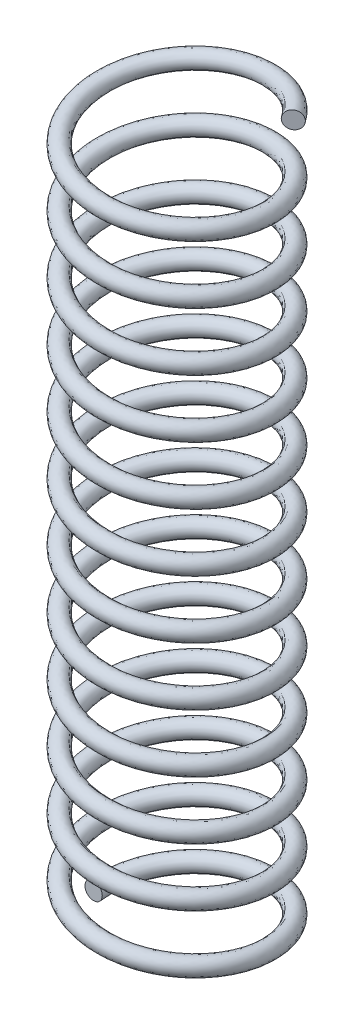
SolidWorks part; units mm, degrees
ref_plane "Front Plane" through (0, 0, 0) normal (0, 0, 1) x (1, 0, 0)
ref_plane "Top Plane" through (0, 0, 0) normal (0, 1, 0) x (1, 0, 0)
ref_plane "Right Plane" through (0, 0, 0) normal (1, 0, 0) x (0, 0, -1)
sketch "Sketch1" plane through (0, 0, 0) normal (0, 1, 0) x (1, 0, 0)
  circle A0 centre (0, 0) radius 5.7531
  dimension "D1" = 11.5062
curve "Helix/Spiral1" pitch 4 height 49.6062 turns 12.4016
sketch "Sketch2" plane through (0, 0, 0) normal (0, 0, 1) x (1, 0, 0)
  circle A0 centre (-5.7531, 0) radius 0.5969
  spline S0 degree 3 poles (-5.7531, 0) (-5.7531, 0.083) (-5.4522, 0.2508) (-4.1674, 0.501) (-2.2454, 0.7516) (0.0199, 1.0021) (2.2821, 1.2527) (4.1955, 1.5032) (5.4674, 1.7538) (5.9034, 2.0043) (5.4369, 2.2548) (4.1391, 2.5054) (2.2085, 2.7559) (-0.0597, 3.0064) (-2.3188, 3.257) (-4.2234, 3.5075) (-5.4823, 3.758) (-5.903, 4.0086) (-5.4212, 4.2591) (-4.1106, 4.5097) (-2.1716, 4.7602) (0.0995, 5.0107) (2.3553, 5.2613) (4.2511, 5.5118) (5.4969, 5.7623) (5.9023, 6.0129) (5.4054, 6.2634) (4.082, 6.5139) (2.1345, 6.7645) (-0.1393, 7.015) (-2.3918, 7.2656) (-4.2786, 7.5161) (-5.5113, 7.7666) (-5.9014, 8.0172) (-5.3892, 8.2677) (-4.0531, 8.5182) (-2.0974, 8.7688) (0.179, 9.0193) (2.4281, 9.2698) (4.3059, 9.5204) (5.5254, 9.7709) (5.9002, 10.0215) (5.3729, 10.272) (4.0241, 10.5225) (2.0601, 10.7731) (-0.2188, 11.0236) (-2.4643, 11.2741) (-4.333, 11.5247) (-5.5393, 11.7752) (-5.8987, 12.0257) (-5.3563, 12.2763) (-3.9949, 12.5268) (-2.0228, 12.7774) (0.2586, 13.0279) (2.5004, 13.2784) (4.36, 13.529) (5.5529, 13.7795) (5.897, 14.03) (5.3394, 14.2806) (3.9655, 14.5311) (1.9854, 14.7816) (-0.2983, 15.0322) (-2.5364, 15.2827) (-4.3867, 15.5333) (-5.5663, 15.7838) (-5.8949, 16.0343) (-5.3223, 16.2849) (-3.936, 16.5354) (-1.9479, 16.7859) (0.338, 17.0365) (2.5723, 17.287) (4.4132, 17.5375) (5.5795, 17.7881) (5.8927, 18.0386) (5.305, 18.2892) (3.9062, 18.5397) (1.9103, 18.7902) (-0.3778, 19.0408) (-2.608, 19.2913) (-4.4395, 19.5418) (-5.5923, 19.7924) (-5.8901, 20.0429) (-5.2874, 20.2934) (-3.8763, 20.544) (-1.8726, 20.7945) (0.4175, 21.0451) (2.6437, 21.2956) (4.4657, 21.5461) (5.605, 21.7967) (5.8873, 22.0472) (5.2696, 22.2977) (3.8462, 22.5483) (1.8348, 22.7988) (-0.4571, 23.0493) (-2.6792, 23.2999) (-4.4916, 23.5504) (-5.6173, 23.801) (-5.8842, 24.0515) (-5.2515, 24.302) (-3.8159, 24.5526) (-1.7969, 24.8031) (0.4968, 25.0536) (2.7146, 25.3042) (4.5173, 25.5547) (5.6294, 25.8052) (5.8809, 26.0558) (5.2332, 26.3063) (3.7855, 26.5569) (1.759, 26.8074) (-0.5364, 27.0579) (-2.7498, 27.3085) (-4.5428, 27.559) (-5.6413, 27.8095) (-5.8773, 28.0601) (-5.2147, 28.3106) (-3.7549, 28.5611) (-1.721, 28.8117) (0.576, 29.0622) (2.785, 29.3128) (4.5681, 29.5633) (5.6529, 29.8138) (5.8734, 30.0644) (5.1959, 30.3149) (3.7241, 30.5654) (1.6829, 30.816) (-0.6156, 31.0665) (-2.82, 31.317) (-4.5932, 31.5676) (-5.6642, 31.8181) (-5.8692, 32.0687) (-5.1769, 32.3192) (-3.6931, 32.5697) (-1.6447, 32.8203) (0.6552, 33.0708) (2.8549, 33.3213) (4.6181, 33.5719) (5.6753, 33.8224) (5.8648, 34.0729) (5.1577, 34.3235) (3.662, 34.574) (1.6064, 34.8246) (-0.6947, 35.0751) (-2.8897, 35.3256) (-4.6428, 35.5762) (-5.6861, 35.8267) (-5.8601, 36.0772) (-5.1382, 36.3278) (-3.6307, 36.5783) (-1.5681, 36.8288) (0.7342, 37.0794) (2.9243, 37.3299) (4.6673, 37.5805) (5.6967, 37.831) (5.8552, 38.0815) (5.1185, 38.3321) (3.5992, 38.5826) (1.5297, 38.8331) (-0.7737, 39.0837) (-2.9588, 39.3342) (-4.6915, 39.5847) (-5.707, 39.8353) (-5.85, 40.0858) (-5.0985, 40.3364) (-3.5676, 40.5869) (-1.4912, 40.8374) (0.8131, 41.088) (2.9932, 41.3385) (4.7156, 41.589) (5.7171, 41.8396) (5.8445, 42.0901) (5.0784, 42.3406) (3.5358, 42.5912) (1.4527, 42.8417) (-0.8525, 43.0923) (-3.0274, 43.3428) (-4.7394, 43.5933) (-5.7269, 43.8439) (-5.8387, 44.0944) (-5.058, 44.3449) (-3.5039, 44.5955) (-1.4141, 44.846) (0.8919, 45.0965) (3.0615, 45.3471) (4.763, 45.5976) (5.7364, 45.8482) (5.8327, 46.0987) (5.0373, 46.3492) (3.4718, 46.5998) (1.3754, 46.8503) (-0.9312, 47.1008) (-3.0954, 47.3514) (-4.7864, 47.6019) (-5.7457, 47.8524) (-5.8265, 48.103) (-5.0165, 48.3535) (-3.4395, 48.6041) (-1.3368, 48.8546) (0.9708, 49.1052) (3.128, 49.3554) (4.2522, 49.5232) (4.6871, 49.6062) knots 0 0 0 0 0.005051 0.010101 0.015152 0.020202 0.025253 0.030303 0.035354 0.040404 0.045455 0.050505 0.055556 0.060606 0.065657 0.070707 0.075758 0.080808 0.085859 0.090909 0.09596 0.10101 0.106061 0.111111 0.116162 0.121212 0.126263 0.131313 0.136364 0.141414 0.146465 0.151515 0.156566 0.161616 0.166667 0.171717 0.176768 0.181818 0.186869 0.191919 0.19697 0.20202 0.207071 0.212121 0.217172 0.222222 0.227273 0.232323 0.237374 0.242424 0.247475 0.252525 0.257576 0.262626 0.267677 0.272727 0.277778 0.282828 0.287879 0.292929 0.29798 0.30303 0.308081 0.313131 0.318182 0.323232 0.328283 0.333333 0.338384 0.343434 0.348485 0.353535 0.358586 0.363636 0.368687 0.373737 0.378788 0.383838 0.388889 0.393939 0.39899 0.40404 0.409091 0.414141 0.419192 0.424242 0.429293 0.434343 0.439394 0.444444 0.449495 0.454545 0.459596 0.464646 0.469697 0.474747 0.479798 0.484848 0.489899 0.494949 0.5 0.505051 0.510101 0.515152 0.520202 0.525253 0.530303 0.535354 0.540404 0.545455 0.550505 0.555556 0.560606 0.565657 0.570707 0.575758 0.580808 0.585859 0.590909 0.59596 0.60101 0.606061 0.611111 0.616162 0.621212 0.626263 0.631313 0.636364 0.641414 0.646465 0.651515 0.656566 0.661616 0.666667 0.671717 0.676768 0.681818 0.686869 0.691919 0.69697 0.70202 0.707071 0.712121 0.717172 0.722222 0.727273 0.732323 0.737374 0.742424 0.747475 0.752525 0.757576 0.762626 0.767677 0.772727 0.777778 0.782828 0.787879 0.792929 0.79798 0.80303 0.808081 0.813131 0.818182 0.823232 0.828283 0.833333 0.838384 0.843434 0.848485 0.853535 0.858586 0.863636 0.868687 0.873737 0.878788 0.883838 0.888889 0.893939 0.89899 0.90404 0.909091 0.914141 0.919192 0.924242 0.929293 0.934343 0.939394 0.944444 0.949495 0.954545 0.959596 0.964646 0.969697 0.974747 0.979798 0.984848 0.989899 0.994949 1 1 1 1 construction
  dimension "D1" = 1.1938
  dimension "D2" = 5.7531
sweep "Sweep1" add profiles "Sketch2" path "Helix/Spiral1"
